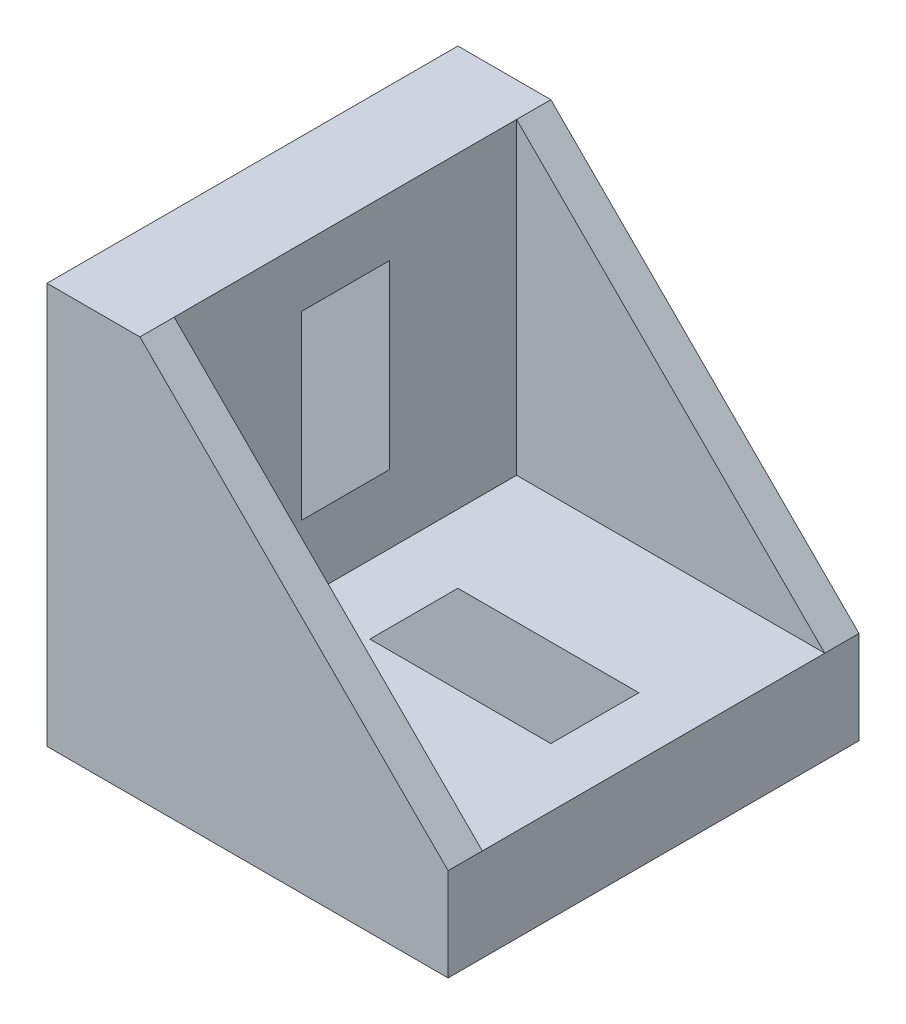
SolidWorks part; units mm, degrees
ref_plane "Front Plane" through (0, 0, 0) normal (0, 0, 1) x (1, 0, 0)
ref_plane "Top Plane" through (0, 0, 0) normal (0, 1, 0) x (1, 0, 0)
ref_plane "Right Plane" through (0, 0, 0) normal (1, 0, 0) x (0, 0, -1)
sketch "Sketch1" plane through (0, 0, 0) normal (0, 0, 1) x (1, 0, 0)
  line L0 (0, 0) -> (0, 41)
  line L1 (41, 9.5) -> (9.5, 41)
  line L4 (9.5, 41) -> (0, 41)
  line L5 (41, 0) -> (0, 0)
  line L7 (41, 9.5) -> (41, 0)
  dimension "D" = 9.5
  dimension "C" = 41
  dimension "B" = 41
extrude "Boss-Extrude1" add sketch "Sketch1" along normal mid plane 42
sketch "Sketch2" plane through (0, 0, 0) normal (0, 0, 1) x (1, 0, 0)
  line L0 (9.5, 41) -> (9.5, 9.5)
  line L1 (9.5, 9.5) -> (41, 9.5)
  line L2 (9.5, 41) -> (41, 9.5)
extrude "Cut-Extrude1" cut sketch "Sketch2" against normal mid plane 35
sketch "Sketch3" plane through (0, 0, 0) normal (0, 0, 1) x (1, 0, 0)
  line L0 (41, 9.5) -> (9.5, 41) construction
  line L1 (0, 35) -> (9.5, 35)
  line L2 (0, 35) -> (0, 7)
  line L3 (0, 7) -> (9.5, 16.5)
  line L4 (9.5, 35) -> (9.5, 16.5)
  line L5 (16.5, 9.5) -> (35, 9.5)
  line L6 (16.5, 9.5) -> (7, 0)
  line L7 (7, 0) -> (35, 0)
  line L8 (35, 9.5) -> (35, 0)
  line L10 (41, 0) -> (0, 0) construction
  line L11 (0, 0) -> (0, 41) construction
  dimension "D1" = 35
  dimension "D2" = 18.5
  dimension "D3" = 35
  dimension "D4" = 18.5
extrude "Cut-Extrude2" cut sketch "Sketch3" against normal mid plane 9
sketch "Sketch4" plane through (0, 0, 0) normal (0, 0, 1) x (1, 0, 0)
  line L0 (0, 41) -> (0, 0) construction
  line L1 (1.2115, 2.3429) -> (0, 1.2348) construction
  line L2 (-0.9777, -4) -> (-1.7275, -3.2384)
  line L3 (0, 3.5355) -> (-4, -0.9777)
  line L4 (-4, -0.9777) -> (-3.2384, -1.7275)
  line L5 (-3.2384, -1.7275) -> (0, 1.2348)
  line L6 (0, 1.2348) -> (0, 3.5355)
  line L7 (-1.7275, -3.2384) -> (1.2348, 0)
  line L8 (0, 0) -> (0, 41) construction
  line L9 (-3.6192, -1.3526) -> (0, 2.3239) construction
  line L10 (1.2348, 0) -> (3.5355, 0)
  line L11 (3.5355, 0) -> (-0.9777, -4)
  line L12 (0, 40.3) -> (0, 37.9992)
  line L13 (0, 37.9992) -> (-3.2384, 35.037)
  line L14 (-3.2384, 35.037) -> (-4, 35.7868)
  line L15 (-4, 35.7868) -> (0, 40.3)
  line L16 (-3.6192, 35.4119) -> (0, 39.0884) construction
  line L17 (0, 39.0884) -> (0.6057, 39.7037) construction
  line L18 (41, 9.5) -> (9.5, 41) construction
  line L19 (25.25, 25.25) -> (0, 0) construction
  line L20 (0, 40.3) -> (1.2115, 39.1074) construction
  line L21 (0, 37.9992) -> (1.2115, 39.1074) construction
  line L22 (0, 3.5355) -> (1.2115, 2.3429) construction
  line L23 (37.9992, 0) -> (35.037, -3.2384)
  line L24 (0.6057, 2.9392) -> (0, 2.3239) construction
  line L25 (35.037, -3.2384) -> (35.7868, -4)
  line L26 (40.3, 0) -> (37.9992, 0)
  line L27 (35.7868, -4) -> (40.3, 0)
  line L28 (-4, -0.9777) -> (-4, 35.7868) construction
  dimension "D1" = 1.7
  dimension "D2" = 5
  dimension "D3" = 6
  dimension "D4" = 1.6001
  dimension "D5" = 0.7
  dimension "D6" = 4
  dimension "D7" = 3.5029
extrude "Boss-Extrude2" add sketch "Sketch4" along normal mid plane 10
